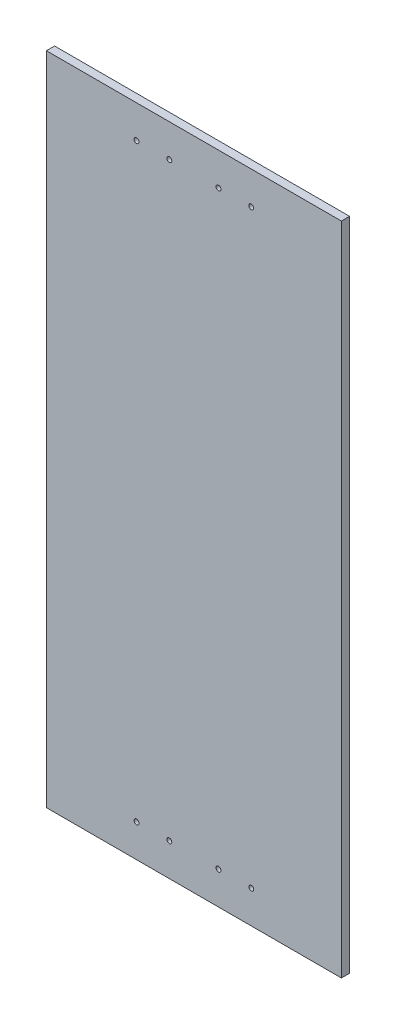
SolidWorks part; units mm, degrees
ref_plane "Alzado" through (0, 0, 0) normal (0, 0, 1) x (1, 0, 0)
ref_plane "Planta" through (0, 0, 0) normal (0, 1, 0) x (1, 0, 0)
ref_plane "Vista lateral" through (0, 0, 0) normal (1, 0, 0) x (0, 0, -1)
sketch "Croquis1" plane through (0, 0, 0) normal (0, 0, 1) x (1, 0, 0)
  line L0 (0, 200) -> (0, -200) construction
  line L1 (-90, -200) -> (90, -200)
  line L2 (-90, -200) -> (-90, 200)
  line L3 (-90, 200) -> (90, 200)
  line L4 (90, -200) -> (90, 200)
  line L5 (-90, -200) -> (90, 200) construction
  line L6 (-90, 200) -> (90, -200) construction
  circle A0 centre (15, -180) radius 1.5
  circle A1 centre (35, -180) radius 1.5
  circle A2 centre (-35, -180) radius 1.5
  circle A3 centre (-15, -180) radius 1.5
  circle A4 centre (15, 180) radius 1.5
  circle A5 centre (35, 180) radius 1.5
  circle A6 centre (-35, 180) radius 1.5
  circle A7 centre (-15, 180) radius 1.5
  point P0 (0, 0)
  dimension "D5" = 3
  dimension "D6" = 3
  dimension "D10" = 3
  dimension "D11" = 3
  dimension "D1" = 400
  dimension "D2" = 180
  dimension "D3" = 15
  dimension "D4" = 20
  dimension "D7" = 20
  dimension "D8" = 15
  dimension "D9" = 20
  dimension "D12" = 20
extrude "Saliente-Extruir1" add sketch "Croquis1" along normal blind 5
